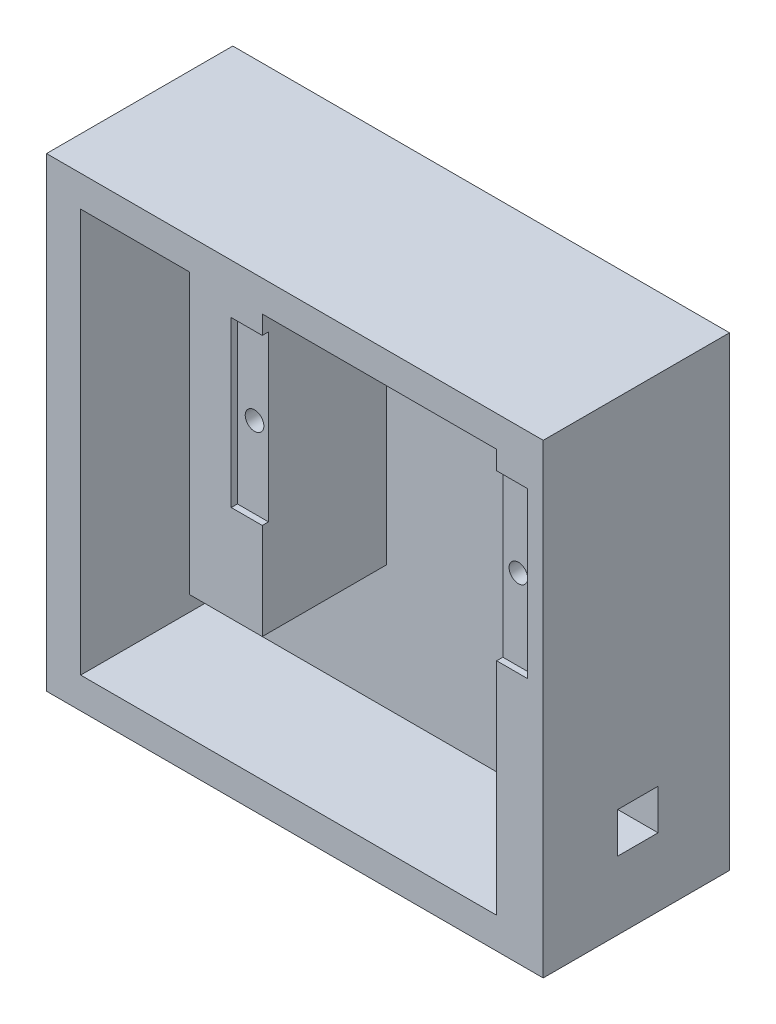
SolidWorks part; units mm, degrees
ref_plane "Front Plane" through (0, 0, 0) normal (0, 0, 1) x (1, 0, 0)
ref_plane "Top Plane" through (0, 0, 0) normal (0, 1, 0) x (1, 0, 0)
ref_plane "Right Plane" through (0, 0, 0) normal (1, 0, 0) x (0, 0, -1)
sketch "Sketch2" plane through (0, 0, 0) normal (0, 0, 1) x (1, 0, 0)
  line L1 (0, 0) -> (-160, 0)
  line L2 (0, 0) -> (0, -150)
  line L3 (0, -150) -> (-160, -150)
  line L4 (-160, 0) -> (-160, -150)
  dimension "D1" = 160
  dimension "D2" = 150
extrude "Boss-Extrude1" add sketch "Sketch2" along normal blind 60
sketch "Sketch3" plane through (0, 0, 60) normal (0, 0, 1) x (1, 0, 0)
  line L0 (0, 0) -> (-160, 0) construction
  line L1 (-90.5, -10) -> (-15, -10)
  line L2 (-90.5, -10) -> (-90.5, -100)
  line L4 (-15, -10) -> (-15, -140)
  line L5 (-149, -140) -> (-15, -140)
  line L6 (-160, -150) -> (0, -150) construction
  line L8 (-160, 0) -> (-160, -150) construction
  line L9 (0, -150) -> (0, 0) construction
  line L10 (-149, -100) -> (-90.5, -100)
  line L11 (-149, -100) -> (-149, -140)
  dimension "D1" = 10
  dimension "D2" = 75.5
  dimension "D3" = 10
  dimension "D4" = 15
  dimension "D5" = 11
  dimension "D7" = 100
extrude "Cut-Extrude1" cut sketch "Sketch3" against normal blind 40
sketch "Sketch4" plane through (0, 0, 60) normal (0, 0, 1) x (1, 0, 0)
  line L1 (0, -150) -> (0, 0) construction
  line L2 (0, 0) -> (-160, 0) construction
  circle A0 centre (-95, -43) radius 3
  circle A1 centre (-10, -43) radius 3
  dimension "D1" = 6
  dimension "D2" = 6
  dimension "D3" = 85
  dimension "D4" = 10
  dimension "D5" = 43
  dimension "D6" = 43
extrude "Cut-Extrude2" cut sketch "Sketch4" against normal up to surface (60 mm away) up to face at (-80, -75, 0)
sketch "Sketch5" plane through (0, 0, 0) normal (1, 0, 0) x (0, 0, -1)
  line L0 (-60, -150) -> (0, -150) construction
  line L1 (-36, -115) -> (-23, -115)
  line L2 (-36, -115) -> (-36, -128)
  line L3 (-36, -128) -> (-23, -128)
  line L4 (-23, -115) -> (-23, -128)
  line L5 (0, -150) -> (0, 0) construction
  point P4 (-29.5, -128)
  dimension "D1" = 22
  dimension "D2" = 13
  dimension "D3" = 13
  dimension "D4" = 23
extrude "Cut-Extrude3" cut sketch "Sketch5" against normal blind 50
sketch "Sketch6" plane through (0, 0, 60) normal (0, 0, 1) x (1, 0, 0)
  line L0 (-90.5, -10) -> (-90.5, -100) construction
  line L1 (-100.5, -16) -> (-90.5, -16)
  line L2 (-100.5, -16) -> (-100.5, -69)
  line L3 (-100.5, -69) -> (-90.5, -69)
  line L4 (-90.5, -16) -> (-90.5, -69)
  line L5 (-15, -140) -> (-15, -10) construction
  line L6 (-15, -16) -> (-5, -16)
  line L7 (-15, -16) -> (-15, -69)
  line L8 (-15, -69) -> (-5, -69)
  line L9 (-5, -16) -> (-5, -69)
  line L10 (0, 0) -> (-160, 0) construction
  point P12 (-95.5, -16)
  dimension "D1" = 53
  dimension "D2" = 53
  dimension "D3" = 16
  dimension "D4" = 16
  dimension "D5" = 10
  dimension "D6" = 10
extrude "Cut-Extrude4" cut sketch "Sketch6" against normal blind 2
sketch "Sketch7" plane through (0, 0, 60) normal (0, 0, 1) x (1, 0, 0)
  line L0 (0, 0) -> (-160, 0) construction
  line L1 (-149, -10) -> (-114, -10)
  line L2 (-149, -10) -> (-149, -140)
  line L3 (-149, -140) -> (-114, -140)
  line L4 (-114, -10) -> (-114, -140)
  line L5 (-160, 0) -> (-160, -150) construction
  line L7 (-160, -150) -> (0, -150) construction
  dimension "D1" = 10
  dimension "D2" = 35
  dimension "D3" = 11
  dimension "D4" = 10
extrude "Cut-Extrude5" cut sketch "Sketch7" against normal blind 40
